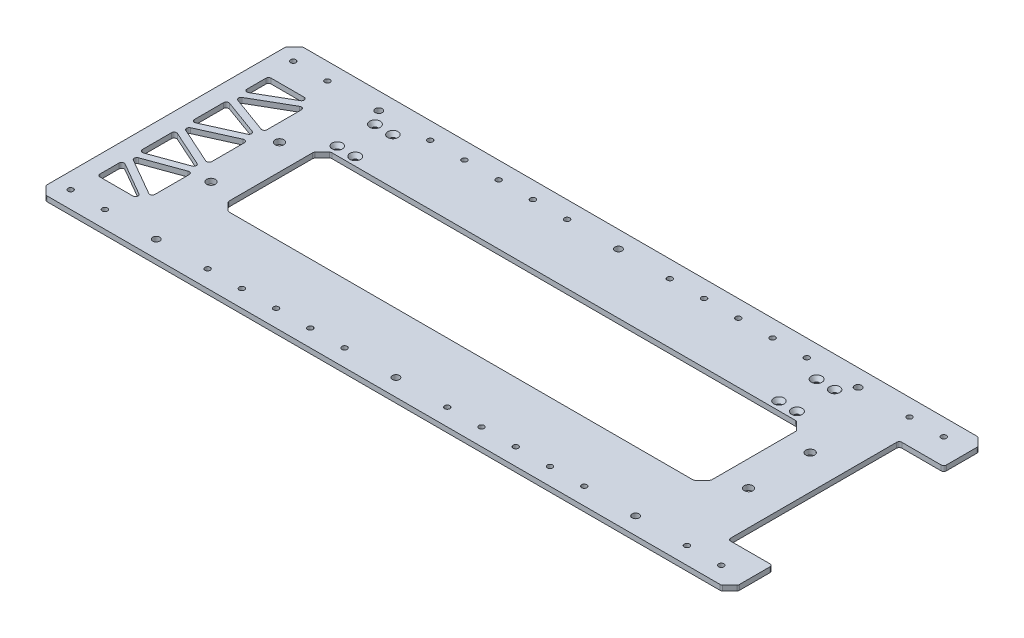
SolidWorks part; units mm, degrees
material "Thornel Mat VMA"
ref_plane "前视基准面" through (0, 0, 0) normal (0, 0, 1) x (1, 0, 0)
ref_plane "上视基准面" through (0, 0, 0) normal (0, 1, 0) x (1, 0, 0)
ref_plane "右视基准面" through (0, 0, 0) normal (1, 0, 0) x (0, 0, -1)
sketch "草图2" plane through (0, 0, 0) normal (0, 1, 0) x (1, 0, 0)
  line L1 (-205, 75) -> (205, 75)
  line L2 (-205, 75) -> (-205, -75)
  line L3 (-205, -75) -> (205, -75)
  line L4 (205, 75) -> (205, -75)
  line L5 (0, -75) -> (0, 75) construction
  line L6 (-205, 0) -> (205, 0) construction
  point P60 (0, 0)
  dimension "D1" = 150
  dimension "D2" = 410
extrude "凸台-拉伸1" add sketch "草图2" along normal blind 3
sketch "草图4" plane through (0, 3, 0) normal (0, 1, 0) x (1, 0, 0)
  line L0 (-195, 65) -> (-195, -65) construction
  line L1 (-195, -65) -> (195, -65) construction
  line L2 (195, -65) -> (195, 65) construction
  line L3 (195, 65) -> (-195, 65) construction
  line L4 (-205, 75) -> (-205, -75)
  line L5 (-205, -75) -> (205, -75)
  line L6 (205, -75) -> (205, 75)
  line L7 (205, 75) -> (-205, 75)
  line L8 (-205, 75) -> (-205, -75) construction
  line L9 (-205, -75) -> (205, -75) construction
  line L10 (205, -75) -> (205, 75) construction
  line L11 (205, 75) -> (-205, 75) construction
  line L12 (0, 0) -> (0, 153.0738) construction
  line L13 (0, 0) -> (225.8253, 0) construction
  circle A0 centre (0, 65) radius 2.05
  circle A1 centre (140, 65) radius 2.05
  circle A2 centre (-140, 65) radius 2.05
  circle A3 centre (-140, -65) radius 2.05
  circle A4 centre (140, -65) radius 2.05
  circle A5 centre (0, -65) radius 2.05
  circle A6 centre (-190, 65) radius 1.55
  circle A7 centre (-170, 65) radius 1.55
  circle A8 centre (-150, 65) radius 1.55 construction
  circle A9 centre (-130, 65) radius 1.55 construction
  circle A10 centre (-110, 65) radius 1.55
  circle A11 centre (-90, 65) radius 1.55
  circle A12 centre (-70, 65) radius 1.55
  circle A13 centre (-50, 65) radius 1.55
  circle A14 centre (-30, 65) radius 1.55
  circle A15 centre (-10, 65) radius 1.55 construction
  circle A16 centre (10, 65) radius 1.55 construction
  circle A17 centre (30, 65) radius 1.55
  circle A18 centre (50, 65) radius 1.55
  circle A19 centre (70, 65) radius 1.55
  circle A20 centre (90, 65) radius 1.55
  circle A21 centre (110, 65) radius 1.55
  circle A22 centre (110, -65) radius 1.55
  circle A23 centre (90, -65) radius 1.55
  circle A24 centre (70, -65) radius 1.55
  circle A25 centre (50, -65) radius 1.55
  circle A26 centre (30, -65) radius 1.55
  circle A27 centre (10, -65) radius 1.55 construction
  circle A28 centre (-10, -65) radius 1.55 construction
  circle A29 centre (-30, -65) radius 1.55
  circle A30 centre (-50, -65) radius 1.55
  circle A31 centre (-70, -65) radius 1.55
  circle A32 centre (-90, -65) radius 1.55
  circle A33 centre (-110, -65) radius 1.55
  circle A34 centre (-130, -65) radius 1.55 construction
  circle A35 centre (-150, -65) radius 1.55 construction
  circle A36 centre (-170, -65) radius 1.55
  circle A37 centre (-190, -65) radius 1.55
  circle A38 centre (130, 65) radius 1.55 construction
  circle A39 centre (150, 65) radius 1.55 construction
  circle A40 centre (170, 65) radius 1.55
  circle A41 centre (190, 65) radius 1.55
  circle A42 centre (170, -65) radius 1.55
  circle A43 centre (150, -65) radius 1.55 construction
  circle A44 centre (130, -65) radius 1.55 construction
  circle A45 centre (190, -65) radius 1.55
  dimension "D3" = 140
  dimension "D4" = 4.1
  dimension "D5" = 15
  dimension "D6" = 3.1
  dimension "D8" = 20
  dimension "D1" = 0
  dimension "D2" = 10
  dimension "D7" = 20
extrude "切除-拉伸1" cut sketch "草图4" against normal blind 3
sketch "草图5" plane through (0, 3, 0) normal (0, 1, 0) x (1, 0, 0)
  line L0 (0, 0) -> (-244.5056, 0) construction
  line L1 (-205, 75) -> (-205, -75) construction
  circle A0 centre (-153, 20) radius 2.55
  circle A1 centre (-153, -20) radius 2.55
  circle A2 centre (159, 18) radius 2.55
  circle A3 centre (159, -18) radius 2.55
  dimension "D1" = 52
  dimension "D2" = 40
  dimension "D3" = 5.1
  dimension "D4" = 36
  dimension "D5" = 312
  dimension "D6" = 5.1
extrude "切除-拉伸2" cut sketch "草图5" against normal blind 3
sketch "草图7" plane through (0, 3, 0) normal (0, 1, 0) x (1, 0, 0)
  line L1 (-138, 30) -> (144, 30)
  line L2 (-138, 30) -> (-138, -30)
  line L3 (-138, -30) -> (144, -30)
  line L4 (144, 30) -> (144, -30)
  line L5 (3, -30) -> (3, 30) construction
  line L6 (-138, 0) -> (144, 0) construction
  circle A0 centre (-153, 20) radius 2.55 construction
  circle A1 centre (159, 18) radius 2.55 construction
  point P44 (3, 0)
  dimension "D1" = 15
  dimension "D2" = 15
  dimension "D3" = 60
extrude "切除-拉伸3" cut sketch "草图7" against normal blind 3
chamfer "倒角1" distance 5 angle 45 8 edges at (-205, 1.5, 75) (205, 1.5, 75) (205, 1.5, -75) (-205, 1.5, -75) (144, 1.5, 30) (144, 1.5, -30) (-138, 1.5, 30) (-138, 1.5, -30)
fillet "圆角1" radius 1.5 16 edges at (-138, 1.5, 25) (-133, 1.5, 30) (139, 1.5, 30) (144, 1.5, 25) (144, 1.5, -25) (139, 1.5, -30) (-138, 1.5, -25) (-133, 1.5, -30) (-200, 1.5, -75) (200, 1.5, -75) (205, 1.5, -70) (205, 1.5, 70) (200, 1.5, 75) (-200, 1.5, 75) (-205, 1.5, 70) (-205, 1.5, -70)
sketch "草图8" plane through (0, 3, 0) normal (0, 1, 0) x (1, 0, 0)
  line L0 (-199.3787, -75) -> (199.3787, -75) construction
  line L1 (-199.3787, 75) -> (-205, 75)
  line L2 (-199.3787, 75) -> (-199.3787, -75)
  line L3 (-199.3787, -75) -> (-205, -75)
  line L4 (-205, 75) -> (-205, -75)
  line L5 (-202.1893, -75) -> (-202.1893, 75) construction
  line L6 (-199.3787, 0) -> (-205, 0) construction
  line L7 (-205, 69.3787) -> (-205, -69.3787) construction
  point P148 (-202.1893, 0)
extrude "切除-拉伸4" cut sketch "草图8" against normal blind 3
chamfer "倒角2" distance 5 angle 45 2 edges at (-199.3787, 1.5, 75) (-199.3787, 1.5, -75)
sketch "草图9" plane through (0, 3, 0) normal (0, 1, 0) x (1, 0, 0)
  line L0 (-199.3787, -70) -> (-199.3787, 70) construction
  line L1 (-189.3787, 50) -> (-163, 50)
  line L2 (-189.3787, 50) -> (-189.3787, -50)
  line L3 (-189.3787, -50) -> (-163, -50)
  line L4 (-163, 50) -> (-163, -50)
  line L5 (-176.1893, -50) -> (-176.1893, 50) construction
  line L6 (-189.3787, 0) -> (-163, 0) construction
  line L7 (0, 0) -> (0, 121.1921) construction
  line L8 (-163, 50) -> (-189.3787, 34.7703)
  line L9 (-189.3787, 30.1515) -> (-163, 45.3812)
  line L10 (-189.3787, 30.1515) -> (-163, 20.5504)
  line L11 (-189.3787, 25.8947) -> (-163, 16.2937)
  line L12 (-163, 16.2937) -> (-189.3787, 4.3885)
  line L13 (-189.3787, 0) -> (-163, 11.9052)
  line L14 (-189.3787, 0) -> (-163, -11.9052)
  line L15 (-163, -16.2937) -> (-189.3787, -4.3885)
  line L16 (-189.3787, -25.8947) -> (-163, -16.2937)
  line L17 (-189.3787, -30.1515) -> (-163, -20.5504)
  line L18 (-189.3787, -30.1515) -> (-163, -45.3812)
  line L19 (-163, -50) -> (-189.3787, -34.7703)
  circle A0 centre (-153, 20) radius 2.55 construction
  circle A1 centre (-170, 65) radius 1.55 construction
  point P92 (-176.1893, 0)
  dimension "D1" = 10
  dimension "D2" = 10
  dimension "D3" = 15
  dimension "D4" = 4
  dimension "D5" = 4
  dimension "D6" = 60
  dimension "D7" = 70
  dimension "D8" = 4
extrude "切除-拉伸5" cut sketch "草图9" against normal blind 20 contours L8 L1 L2 | L9 L10 L4 | L12 L11 L2 | L13 L14 L4 | L2 L16 L15 | L17 L18 L4 | L3 L19 L2
sketch "草图11" plane through (0, 3, 0) normal (0, 1, 0) x (1, 0, 0)
  line L0 (-138, 24.3787) -> (-138, -24.3787) construction
  line L1 (144, -24.3787) -> (144, 24.3787) construction
  line L2 (-132.3787, -30) -> (138.3787, -30) construction
  line L5 (0, 0) -> (-74.0452, 0) construction
  circle A0 centre (134.25, -35) radius 1.6
  circle A1 centre (123.75, -57) radius 1.6
  circle A2 centre (-123.75, -35) radius 1.6
  circle A3 centre (-134.25, -57) radius 1.6
  circle A4 centre (123.75, 57) radius 1.6
  circle A5 centre (134.25, 35) radius 1.6
  circle A6 centre (-134.25, 57) radius 1.6
  circle A7 centre (-123.75, 35) radius 1.6
  line B0 (-123.75, -57) -> (-123.75, -35) construction
  line B1 (-123.75, -57) -> (-134.25, -57) construction
  line B2 (-134.25, -57) -> (-134.25, -35) construction
  line B3 (-123.75, -35) -> (-134.25, -35) construction
  line B4 (-134.25, -46) -> (-123.75, -46) construction
  line B5 (-129, -57) -> (-129, -35) construction
  circle B6 centre (-134.25, -35) radius 1.5
  circle B7 centre (-123.75, -57) radius 1.5
  line B8 (134.25, -57) -> (134.25, -35) construction
  line B9 (134.25, -57) -> (123.75, -57) construction
  line B10 (123.75, -57) -> (123.75, -35) construction
  line B11 (134.25, -35) -> (123.75, -35) construction
  line B12 (123.75, -46) -> (134.25, -46) construction
  line B13 (129, -57) -> (129, -35) construction
  circle B14 centre (123.75, -35) radius 1.5
  circle B15 centre (134.25, -57) radius 1.5
  line B16 (134.25, 57) -> (134.25, 35) construction
  line B17 (134.25, 57) -> (123.75, 57) construction
  line B18 (123.75, 57) -> (123.75, 35) construction
  line B19 (134.25, 35) -> (123.75, 35) construction
  line B20 (123.75, 46) -> (134.25, 46) construction
  line B21 (129, 57) -> (129, 35) construction
  circle B22 centre (123.75, 35) radius 1.5
  circle B23 centre (134.25, 57) radius 1.5
  line B24 (-123.75, 57) -> (-123.75, 35) construction
  line B25 (-123.75, 57) -> (-134.25, 57) construction
  line B26 (-134.25, 57) -> (-134.25, 35) construction
  line B27 (-123.75, 35) -> (-134.25, 35) construction
  line B28 (-134.25, 46) -> (-123.75, 46) construction
  line B29 (-129, 57) -> (-129, 35) construction
  circle B30 centre (-134.25, 35) radius 1.5
  circle B31 centre (-123.75, 57) radius 1.5
  dimension "D5" = 3.2
  dimension "D6" = 3.2
  dimension "D7" = 3.2
  dimension "D8" = 3.2
  dimension "D1" = 9
  dimension "D2" = 15
  dimension "D3" = 5
  dimension "D4" = 5
sketch_block_instance "块-碰撞开光-1"
sketch_block "块-碰撞开光" parameters "D1"=3, "D2"=3, "D3"=10.5, "D4"=22
sketch_block_instance "块-碰撞开光-2"
sketch_block_instance "块-碰撞开光-4"
sketch_block_instance "块-碰撞开光-5"
extrude "切除-拉伸6" cut sketch "草图11" against normal blind 10 contours A6 | B31 | B30 | A7 | A4 | B23 | B22 | A5
sketch "草图12" plane through (0, 3, 0) normal (0, 1, 0) x (1, 0, 0)
  line L0 (205, -69.3787) -> (205, 69.3787) construction
  line L1 (205, 50) -> (179, 50)
  line L2 (205, 50) -> (205, -50)
  line L3 (205, -50) -> (179, -50)
  line L4 (179, 50) -> (179, -50)
  line L5 (192, -50) -> (192, 50) construction
  line L6 (205, 0) -> (179, 0) construction
  circle A0 centre (190, 65) radius 1.55 construction
  circle A1 centre (190, -65) radius 1.55 construction
  circle A2 centre (159, 18) radius 2.55 construction
  point P96 (192, 0)
  dimension "D1" = 15
  dimension "D2" = 15
  dimension "D3" = 20
extrude "切除-拉伸7" cut sketch "草图12" against normal blind 10
fillet "圆角2" radius 1.5 29 edges at (205, 1.5, 50) (-194.3787, 1.5, 75) (-199.3787, 1.5, 70) (-199.3787, 1.5, -70) (-194.3787, 1.5, -75) (179, 1.5, -50) (179, 1.5, 50) (205, 1.5, -50) (-163, 1.5, -11.9052) (-163, 1.5, 11.9052) (-189.3787, 1.5, 0) (-163, 1.5, 16.2937) (-189.3787, 1.5, 25.8947) (-189.3787, 1.5, 4.3885) (-189.3787, 1.5, -4.3885) (-189.3787, 1.5, -25.8947) (-163, 1.5, -16.2937) (-189.3787, 1.5, 34.7703) (-163, 1.5, 50) (-189.3787, 1.5, 50) (-189.3787, 1.5, -34.7703) (-189.3787, 1.5, -50) (-163, 1.5, 20.5504) (-163, 1.5, 45.3812) (-189.3787, 1.5, 30.1515) (-163, 1.5, -45.3812) (-163, 1.5, -20.5504) (-189.3787, 1.5, -30.1515) (-163, 1.5, -50)
chamfer "倒角3" distance 2.5 distance2 1.5 8 edges at (123.75, 3, -55.4) (-123.75, 3, -33.4) (-134.25, 3, -33.5) (-134.25, 3, -55.4) (-123.75, 3, -55.5) (123.75, 3, -33.5) (134.25, 3, -33.4) (134.25, 3, -55.5)
